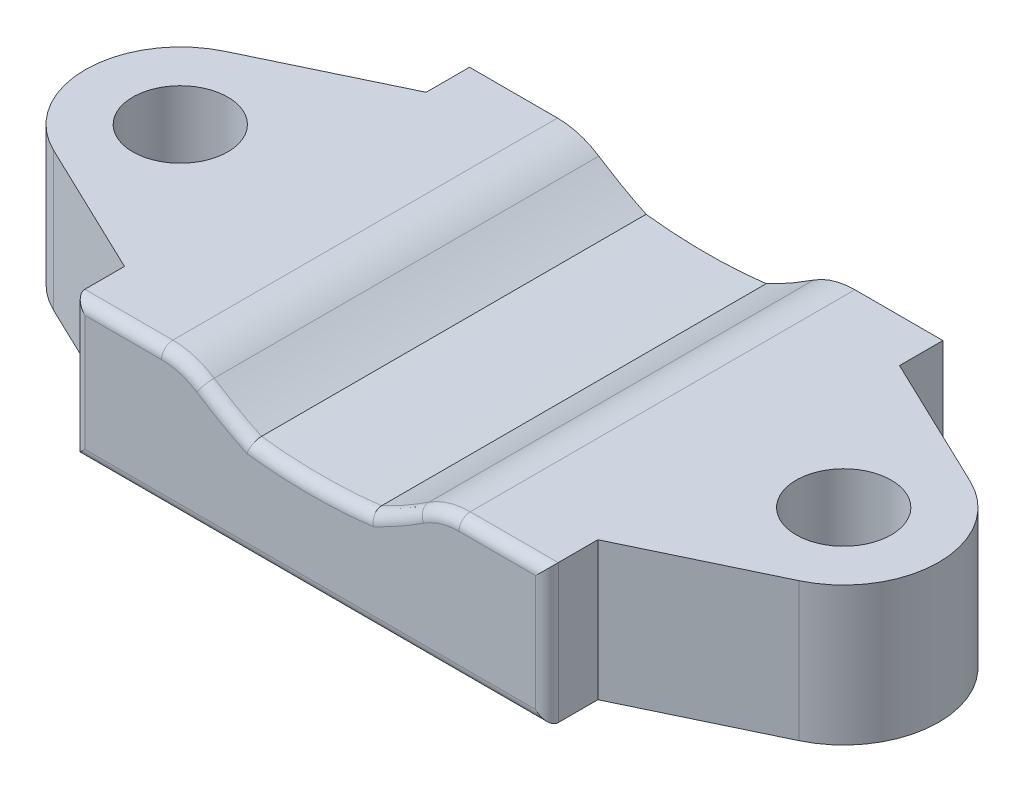
SolidWorks part; units mm, degrees
ref_plane "Front Plane" through (0, 0, 0) normal (0, 0, 1) x (1, 0, 0)
ref_plane "Top Plane" through (0, 0, 0) normal (0, 1, 0) x (1, 0, 0)
ref_plane "Right Plane" through (0, 0, 0) normal (1, 0, 0) x (0, 0, -1)
sketch "Sketch2" plane through (0, 0, 0) normal (0, 1, 0) x (1, 0, 0)
  line L0 (-7.9722, 13.335) -> (7.9722, 13.335)
  line L1 (-7.9722, 13.589) -> (7.9722, 13.589)
  line L2 (-7.9722, 13.589) -> (-7.9722, 0)
  line L3 (-7.9722, 0) -> (7.9722, 0)
  line L4 (7.9722, 13.589) -> (7.9722, 0)
  line L5 (-7.9722, 15.8021) -> (-7.9722, 13.589)
  line L6 (-7.9722, 12.4302) -> (-7.9722, 10.9505)
  line L7 (0, -2.7857) -> (0, 17.8226) construction
  line L8 (-7.9722, 1.7145) -> (-12.5544, 3.9077)
  line L9 (-7.9722, 2.6385) -> (-7.9722, 0)
  line L10 (-7.9722, 0) -> (-5.0083, 0)
  line L11 (-5.0083, 0) -> (-5.0083, 15.379)
  line L12 (-5.0083, 15.379) -> (-6.4229, 15.379)
  line L13 (5.0083, 15.379) -> (5.0083, 0)
  line L14 (5.0083, 0) -> (7.9722, 0)
  line L15 (7.9722, 0) -> (7.9722, 2.6385)
  line L16 (-12.5544, 9.6813) -> (-7.9722, 11.8745)
  line L18 (7.9722, 10.9505) -> (7.9722, 12.4302)
  line L19 (7.9722, 13.589) -> (7.9722, 15.8021)
  line L20 (6.4229, 15.379) -> (5.0083, 15.379)
  line L21 (12.5544, 9.6813) -> (7.9722, 11.8745)
  line L22 (7.9722, 11.8745) -> (7.9722, 1.7145)
  line L23 (7.9722, 1.7145) -> (12.5544, 3.9077)
  line L24 (-19.6754, 6.7945) -> (16.0047, 6.7945) construction
  arc A0 (-8.8876, 13.9849) -> (-7.9722, 13.589) centre (-6.4229, 18.427) ccw
  arc A1 (-7.9722, 12.4302) -> (-8.8876, 13.9849) centre (-9.7502, 12.4302) ccw
  circle A2 centre (-11.1726, 6.7945) radius 1.6002
  arc A3 (-7.9722, 15.8021) -> (-6.4229, 15.379) centre (-6.4229, 18.427) ccw
  arc A4 (-12.5544, 3.9077) -> (-12.5544, 9.6813) centre (-11.1726, 6.7945) cw
  arc A5 (8.8876, 13.9849) -> (7.9722, 12.4302) centre (9.7502, 12.4302) ccw
  arc A6 (7.9722, 13.589) -> (8.8876, 13.9849) centre (6.4229, 18.427) ccw
  arc A7 (6.4229, 15.379) -> (7.9722, 15.8021) centre (6.4229, 18.427) ccw
  arc A10 (12.5544, 3.9077) -> (12.5544, 9.6813) centre (11.1726, 6.7945) ccw
  circle A11 centre (11.1726, 6.7945) radius 1.6002
  dimension "D1" = 0.254
extrude "Boss-Extrude1" add sketch "Sketch2" along normal blind 4.6675
sketch "Sketch1" plane through (0, 0, 0) normal (0, 0, 1) x (1, 0, 0)
  line L0 (-7.9722, 4.6675) -> (-5.0083, 4.6675)
  line L1 (0, -4.0352) -> (0, 16.4512) construction
  line L2 (7.9722, 4.6675) -> (5.0083, 4.6675)
  line L3 (7.9722, -2.4125) -> (7.9722, 4.6675)
  line L4 (7.9722, 4.6675) -> (-7.9722, 4.6675)
  line L5 (-7.9722, 4.6675) -> (-7.9722, -2.4125)
  line L6 (-7.9722, -2.4125) -> (7.9722, -2.4125)
  line L7 (-2.0229, 3.352) -> (2.0229, 3.352)
  line L11 (-7.9722, 0) -> (7.9722, 0)
  line L12 (7.9722, 0) -> (7.9722, 4.6675)
  line L13 (7.9722, 4.6675) -> (-7.9722, 4.6675)
  line L14 (-7.9722, 4.6675) -> (-7.9722, 0)
  line L15 (-7.9722, 0) -> (7.9722, 0)
  line L16 (7.9722, 0) -> (7.9722, 4.6675)
  line L17 (7.9722, 4.6675) -> (-7.9722, 4.6675)
  line L18 (-7.9722, 4.6675) -> (-7.9722, 0)
  circle A0 centre (0, 4.6675) radius 2.413
  arc A1 (-0.8972, 2.87) -> (0.8972, 2.87) centre (0, 5.2463) ccw
  arc A2 (5.0083, 4.6675) -> (3.6162, 4.2521) centre (5.0083, 2.1275) ccw
  arc A3 (-5.0083, 4.6675) -> (-3.6162, 4.2521) centre (-5.0083, 2.1275) cw
  spline S0 degree 3 poles (-3.6162, 4.2521) (-3.3878, 4.1024) (-2.5196, 3.5694) (-1.5987, 3.1349) (-0.8972, 2.87) knots 0.154249 0.154249 0.154249 0.154249 0.327775 0.801446 0.801446 0.801446 0.801446
  spline S1 degree 3 poles (3.6162, 4.2521) (3.3878, 4.1024) (2.5196, 3.5694) (1.5987, 3.1349) (0.8972, 2.87) knots 0.154249 0.154249 0.154249 0.154249 0.327775 0.801446 0.801446 0.801446 0.801446
  spline S2 degree 2 poles (-2.0229, 3.352) (0, 2.2987) (2.0229, 3.352) knots 0 0 0 1 1 1
  spline S3 degree 2 poles (-2.0229, 3.352) (0, 3.1058) (2.0229, 3.352) knots 0 0 0 1 1 1
  spline S4 degree 1 poles (-3.6162, 4.2521) (-2.7778, 3.8237) knots 0 0 1 1
  spline S5 degree 2 poles (-5.0083, 4.6675) (-4.9305, 4.6663) (-4.854, 4.6628) knots 0 0 0 0.042864 0.042864 0.042864
  spline S6 degree 2 poles (5.0083, 4.6675) (4.9305, 4.6663) (4.854, 4.6628) knots 0 0 0 0.042864 0.042864 0.042864
  dimension "D1" = 4.826
  dimension "D2" = 2.54
  dimension "D3" = 2.54
  dimension "D5" = 2.54
  dimension "D4" = 2.964
  dimension "D6" = 0.4154
  dimension "D7" = 0
extrude "Cut-Extrude1" cut sketch "Sketch1" against normal through all contours A3 S0 A0 L4 | A1 L1 L4 A0 S0 | L1 A1 S1 A0 L17 | S1 A2 L4 A0 | S3 L1 L7 | L1 S3 L7
fillet "Fillet4" radius 0.381 10 edges at (4.2819, 4.5614, 0) (6.4902, 4.6675, 0) (7.9722, 2.3337, 0) (0, 0, 0) (-7.9722, 2.3337, 0) (-6.4902, 4.6675, 0) (-4.2819, 4.5614, 0)
